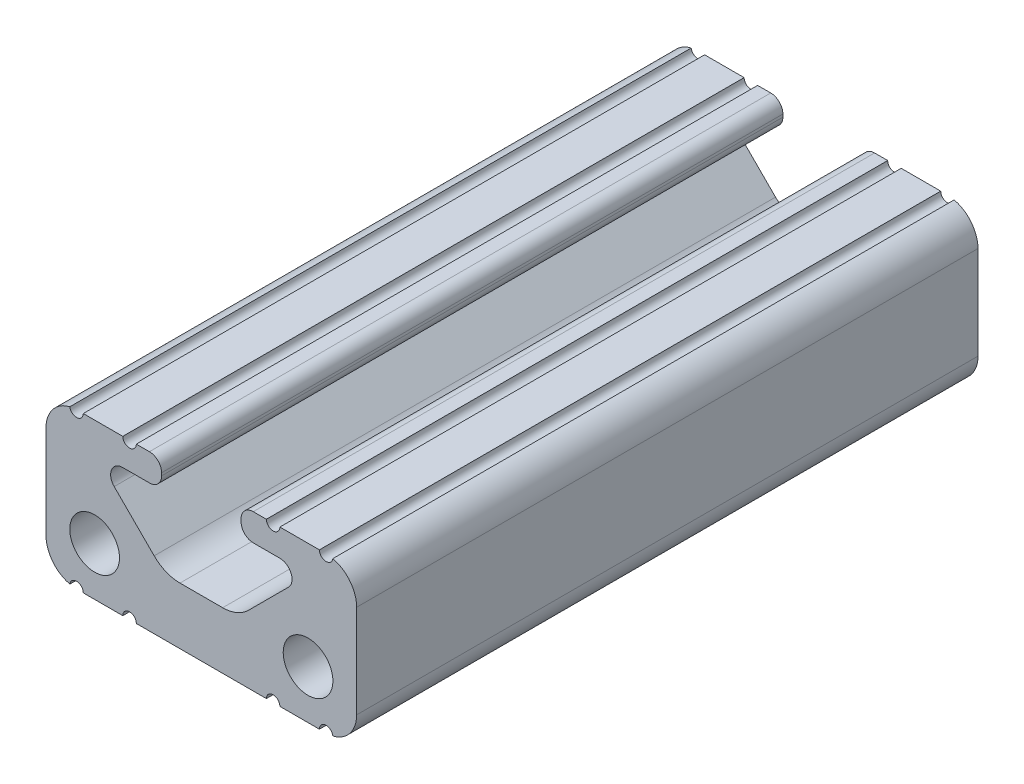
SolidWorks part; units mm, degrees
ref_plane "Front Plane" through (0, 0, 0) normal (0, 0, 1) x (1, 0, 0)
ref_plane "Top Plane" through (0, 0, 0) normal (0, 1, 0) x (1, 0, 0)
ref_plane "Right Plane" through (0, 0, 0) normal (1, 0, 0) x (0, 0, -1)
sketch "Sketch1" plane through (0, 0, 0) normal (0, 0, 1) x (1, 0, 0)
  line L0 (0, 6.35) -> (0, -6.35) construction
  line L1 (0, -6.35) -> (12.7, -6.35)
  line L2 (12.7, -6.35) -> (12.7, 6.35)
  line L3 (12.7, 6.35) -> (3.2512, 6.35)
  line L4 (3.2512, 6.35) -> (3.2512, 4.1402)
  line L5 (3.2512, 4.1402) -> (6.4224, 4.1402)
  line L6 (7.1255, 2.4426) -> (2.9811, -1.7018)
  line L7 (2.9811, -1.7018) -> (0, -1.7018)
  circle A0 centre (8.7249, -2.3876) radius 2.032
  arc A1 (6.4224, 4.1402) -> (7.1255, 2.4426) centre (6.4224, 3.1458) cw
  dimension "Center Hole Diameter" = 4.064
  dimension "D3" = 0.9944
  dimension "Rail Height" = 25.4
  dimension "Rail Width" = 12.7
  dimension "Hole CtoC" = 17.4498
  dimension "D1" = 3.9624
  dimension "T-Slot Width" = 6.5024
  dimension "Thickness" = 2.2098
  dimension "Inner Slot Width" = 14.8336
  dimension "Slot Depth" = 5.842
  dimension "D2" = 45
sketch "Sketch2" plane through (0, 0, 0) normal (1, 0, 0) x (0, 0, -1)
  line L0 (-152.4, -6.35) -> (152.4, -6.35) construction
  line L1 (-127, 0) -> (127, 0) construction
  dimension "Length" = 304.8
sketch "Sketch3" plane through (0, 0, 0) normal (0, 0, 1) x (1, 0, 0)
  line L0 (3.2512, 6.35) -> (3.2512, 4.1402) construction
  line L1 (12.7, 6.35) -> (3.2512, 6.35) construction
  line L2 (3.2512, 4.1402) -> (6.4224, 4.1402) construction
  line L3 (3.2512, 5.3556) -> (3.2512, 5.1346)
  line L4 (12.7, -6.35) -> (12.7, 6.35) construction
  line L5 (0, -6.35) -> (12.7, -6.35) construction
  line L6 (2.9811, -1.7018) -> (0, -1.7018) construction
  line L7 (7.1255, 2.4426) -> (2.9811, -1.7018) construction
  line L8 (0, -1.7018) -> (1.7454, -1.7018)
  line L9 (4.2456, 4.1402) -> (6.4224, 4.1402)
  line L10 (3.8549, -0.828) -> (7.1255, 2.4426)
  line L11 (0, -1.7018) -> (0, -6.35)
  line L12 (0, -6.35) -> (10.16, -6.35)
  line L13 (12.7, -3.81) -> (12.7, 3.81)
  line L14 (4.2456, 6.35) -> (10.16, 6.35)
  arc A0 (3.2512, 5.3556) -> (4.2456, 6.35) centre (4.2456, 5.3556) cw
  arc A1 (3.2512, 5.1346) -> (4.2456, 4.1402) centre (4.2456, 5.1346) ccw
  arc A2 (7.1255, 2.4426) -> (6.4224, 4.1402) centre (6.4224, 3.1458) ccw construction
  arc A3 (10.16, 6.35) -> (12.7, 3.81) centre (10.16, 3.81) cw
  arc A4 (10.16, -6.35) -> (12.7, -3.81) centre (10.16, -3.81) ccw
  arc A5 (7.1255, 2.4426) -> (6.4224, 4.1402) centre (6.4224, 3.1458) ccw
  circle A6 centre (8.7249, -2.3876) radius 2.032 construction
  circle A7 centre (8.7249, -2.3876) radius 2.032
  arc A8 (1.7454, -1.7018) -> (3.8549, -0.828) centre (1.7454, 1.2814) ccw
  dimension "D2" = 2.9832
  dimension "D1" = 2.54
extrude "Boss-Extrude1" add sketch "Sketch3" along normal mid plane 304.8
sketch "Sketch4" plane through (0, 0, 0) normal (0, 0, 1) x (1, 0, 0)
  line L0 (12.7, 6.35) -> (3.2512, 6.35) construction
  line L1 (0, -6.35) -> (12.7, -6.35) construction
  line L2 (10.7569, -2.3876) -> (10.7569, 6.35) construction
  line L3 (6.4224, 3.1458) -> (6.4224, 6.35) construction
  circle A0 centre (5.8699, 6.35) radius 0.5524
  circle A1 centre (10.2045, 6.35) radius 0.5524
  circle A2 centre (5.8699, -6.35) radius 0.5524
  circle A3 centre (10.2045, -6.35) radius 0.5524
  circle A4 centre (8.7249, -2.3876) radius 2.032 construction
  dimension "D1" = 1.1049
extrude "Cut-Extrude1" cut sketch "Sketch4" against normal through all both and the other way through all
mirror "Mirror1" about plane through (0, 0, 0) normal (1, 0, 0) of bodies 135
sketch "Sketch5" plane through (0, 0, 152.4) normal (0, 0, 1) x (1, 0, 0)
  line L16 (9.652, 6.35) -> (6.4224, 6.35)
  line L17 (5.3175, 6.35) -> (4.2456, 6.35)
  line L18 (3.2512, 5.3556) -> (3.2512, 5.1346)
  line L19 (4.2456, 4.1402) -> (6.4224, 4.1402)
  line L20 (7.1255, 2.4426) -> (3.8549, -0.828)
  line L21 (1.7454, -1.7018) -> (-1.7454, -1.7018)
  line L22 (-3.8549, -0.828) -> (-7.1255, 2.4426)
  line L23 (-6.4224, 4.1402) -> (-4.2456, 4.1402)
  line L24 (-3.2512, 5.1346) -> (-3.2512, 5.3556)
  line L25 (-4.2456, 6.35) -> (-5.3175, 6.35)
  line L26 (-6.4224, 6.35) -> (-9.652, 6.35)
  line L27 (-12.7, 3.81) -> (-12.7, -3.81)
  line L28 (-9.652, -6.35) -> (-6.4224, -6.35)
  line L29 (-5.3175, -6.35) -> (5.3175, -6.35)
  line L30 (6.4224, -6.35) -> (9.652, -6.35)
  line L31 (12.7, -3.81) -> (12.7, 3.81)
  line L32 (9.652, 6.35) -> (6.4224, 6.35)
  line L33 (5.3175, 6.35) -> (4.2456, 6.35)
  line L34 (3.2512, 5.3556) -> (3.2512, 5.1346)
  line L35 (4.2456, 4.1402) -> (6.4224, 4.1402)
  line L36 (7.1255, 2.4426) -> (3.8549, -0.828)
  line L37 (1.7454, -1.7018) -> (-1.7454, -1.7018)
  line L38 (-3.8549, -0.828) -> (-7.1255, 2.4426)
  line L39 (-6.4224, 4.1402) -> (-4.2456, 4.1402)
  line L40 (-3.2512, 5.1346) -> (-3.2512, 5.3556)
  line L41 (-4.2456, 6.35) -> (-5.3175, 6.35)
  line L42 (-6.4224, 6.35) -> (-9.652, 6.35)
  line L43 (-12.7, 3.81) -> (-12.7, -3.81)
  line L44 (-9.652, -6.35) -> (-6.4224, -6.35)
  line L45 (-5.3175, -6.35) -> (5.3175, -6.35)
  line L46 (6.4224, -6.35) -> (9.652, -6.35)
  line L47 (12.7, -3.81) -> (12.7, 3.81)
  arc A20 (12.7, 3.81) -> (10.7524, 6.2799) centre (10.16, 3.81) ccw
  arc A21 (9.652, 6.35) -> (10.7524, 6.2799) centre (10.2045, 6.35) ccw
  arc A22 (5.3175, 6.35) -> (6.4224, 6.35) centre (5.8699, 6.35) ccw
  arc A23 (4.2456, 6.35) -> (3.2512, 5.3556) centre (4.2456, 5.3556) ccw
  arc A24 (3.2512, 5.1346) -> (4.2456, 4.1402) centre (4.2456, 5.1346) ccw
  arc A25 (7.1255, 2.4426) -> (6.4224, 4.1402) centre (6.4224, 3.1458) ccw
  arc A26 (1.7454, -1.7018) -> (3.8549, -0.828) centre (1.7454, 1.2814) ccw
  arc A27 (-3.8549, -0.828) -> (-1.7454, -1.7018) centre (-1.7454, 1.2814) ccw
  arc A28 (-6.4224, 4.1402) -> (-7.1255, 2.4426) centre (-6.4224, 3.1458) ccw
  arc A29 (-4.2456, 4.1402) -> (-3.2512, 5.1346) centre (-4.2456, 5.1346) ccw
  arc A30 (-3.2512, 5.3556) -> (-4.2456, 6.35) centre (-4.2456, 5.3556) ccw
  arc A31 (-6.4224, 6.35) -> (-5.3175, 6.35) centre (-5.8699, 6.35) ccw
  arc A32 (-10.7524, 6.2799) -> (-9.652, 6.35) centre (-10.2045, 6.35) ccw
  arc A33 (-10.7524, 6.2799) -> (-12.7, 3.81) centre (-10.16, 3.81) ccw
  arc A34 (-12.7, -3.81) -> (-10.7524, -6.2799) centre (-10.16, -3.81) ccw
  arc A35 (-9.652, -6.35) -> (-10.7524, -6.2799) centre (-10.2045, -6.35) ccw
  arc A36 (-5.3175, -6.35) -> (-6.4224, -6.35) centre (-5.8699, -6.35) ccw
  arc A37 (6.4224, -6.35) -> (5.3175, -6.35) centre (5.8699, -6.35) ccw
  arc A38 (10.7524, -6.2799) -> (9.652, -6.35) centre (10.2045, -6.35) ccw
  arc A39 (10.7524, -6.2799) -> (12.7, -3.81) centre (10.16, -3.81) ccw
  arc A40 (12.7, 3.81) -> (10.7524, 6.2799) centre (10.16, 3.81) ccw
  arc A41 (9.652, 6.35) -> (10.7524, 6.2799) centre (10.2045, 6.35) ccw
  arc A42 (5.3175, 6.35) -> (6.4224, 6.35) centre (5.8699, 6.35) ccw
  arc A43 (4.2456, 6.35) -> (3.2512, 5.3556) centre (4.2456, 5.3556) ccw
  arc A44 (3.2512, 5.1346) -> (4.2456, 4.1402) centre (4.2456, 5.1346) ccw
  arc A45 (7.1255, 2.4426) -> (6.4224, 4.1402) centre (6.4224, 3.1458) ccw
  arc A46 (1.7454, -1.7018) -> (3.8549, -0.828) centre (1.7454, 1.2814) ccw
  arc A47 (-3.8549, -0.828) -> (-1.7454, -1.7018) centre (-1.7454, 1.2814) ccw
  arc A48 (-6.4224, 4.1402) -> (-7.1255, 2.4426) centre (-6.4224, 3.1458) ccw
  arc A49 (-4.2456, 4.1402) -> (-3.2512, 5.1346) centre (-4.2456, 5.1346) ccw
  arc A50 (-3.2512, 5.3556) -> (-4.2456, 6.35) centre (-4.2456, 5.3556) ccw
  arc A51 (-6.4224, 6.35) -> (-5.3175, 6.35) centre (-5.8699, 6.35) ccw
  arc A52 (-10.7524, 6.2799) -> (-9.652, 6.35) centre (-10.2045, 6.35) ccw
  arc A53 (-10.7524, 6.2799) -> (-12.7, 3.81) centre (-10.16, 3.81) ccw
  arc A54 (-12.7, -3.81) -> (-10.7524, -6.2799) centre (-10.16, -3.81) ccw
  arc A55 (-9.652, -6.35) -> (-10.7524, -6.2799) centre (-10.2045, -6.35) ccw
  arc A56 (-5.3175, -6.35) -> (-6.4224, -6.35) centre (-5.8699, -6.35) ccw
  arc A57 (6.4224, -6.35) -> (5.3175, -6.35) centre (5.8699, -6.35) ccw
  arc A58 (10.7524, -6.2799) -> (9.652, -6.35) centre (10.2045, -6.35) ccw
  arc A59 (10.7524, -6.2799) -> (12.7, -3.81) centre (10.16, -3.81) ccw
  dimension "D1" = 0
extrude "Cut-Extrude2" cut sketch "Sketch5" against normal offset from surface (254 mm away) 50.8 up to face at (0, 1.3921, -152.4)
equation "\"D3@Sketch1\"=\"Thickness@Sketch1\"*0.45"
equation "\"D1@Sketch3\"=\"Rail Width@Sketch1\"*0.2"
equation "\"D2@Sketch3\"=\"D3@Sketch1\"*3"
equation "\"D1@Boss-Extrude1\"=\"length@sketch2\""
equation "\"D1@Sketch4\"=\"Thickness@Sketch1\"*0.5"
